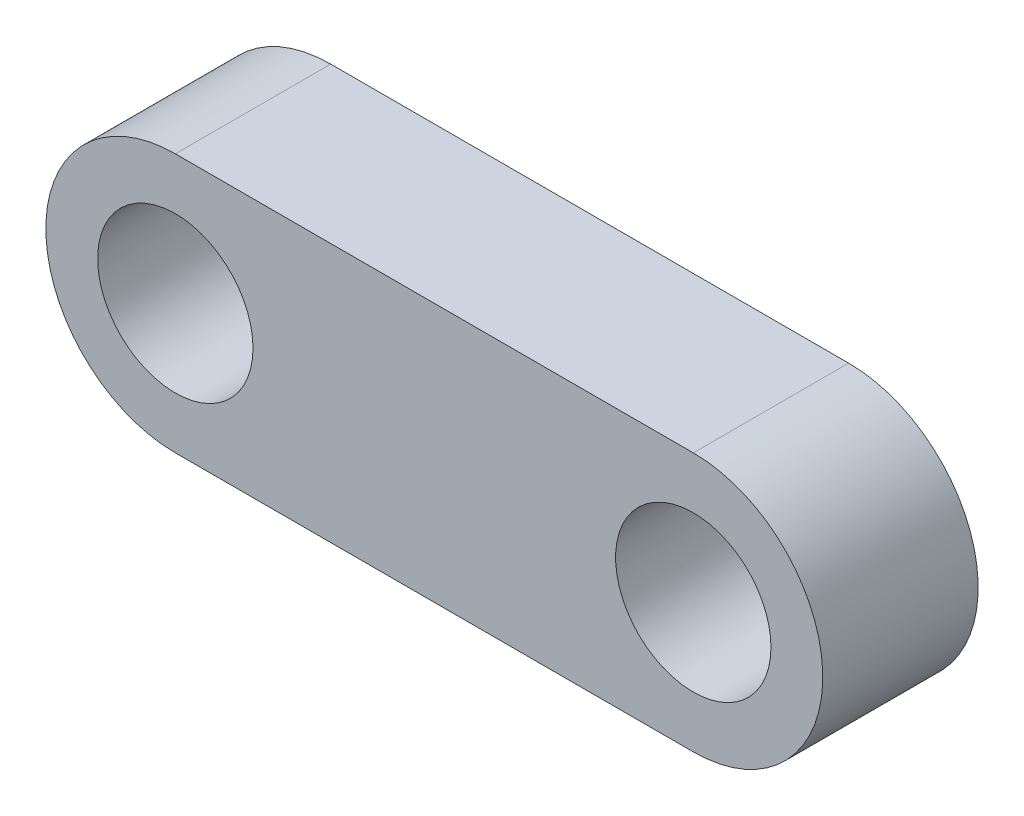
SolidWorks part; units mm, degrees
ref_plane "Plan de face" through (0, 0, 0) normal (0, 0, 1) x (1, 0, 0)
ref_plane "Plan de dessus" through (0, 0, 0) normal (0, 1, 0) x (1, 0, 0)
ref_plane "Plan de droite" through (0, 0, 0) normal (1, 0, 0) x (0, 0, -1)
sketch "Esquisse1" plane through (0, 0, 0) normal (0, 0, 1) x (1, 0, 0)
  line L0 (-5, 0) -> (5, 0) construction
  line L1 (-5, 2.5) -> (5, 2.5)
  line L2 (-5, -2.5) -> (5, -2.5)
  arc A0 (-5, 2.5) -> (-5, -2.5) centre (-5, 0) ccw
  arc A1 (5, -2.5) -> (5, 2.5) centre (5, 0) ccw
  circle A2 centre (-5, 0) radius 1.5
  circle A3 centre (5, 0) radius 1.5
  point P2 (0, 0)
  dimension "D2" = 2.5
  dimension "D3" = 3
  dimension "D4" = 3
  dimension "D1" = 10
extrude "Boss.-Extru.1" add sketch "Esquisse1" along normal blind 3
